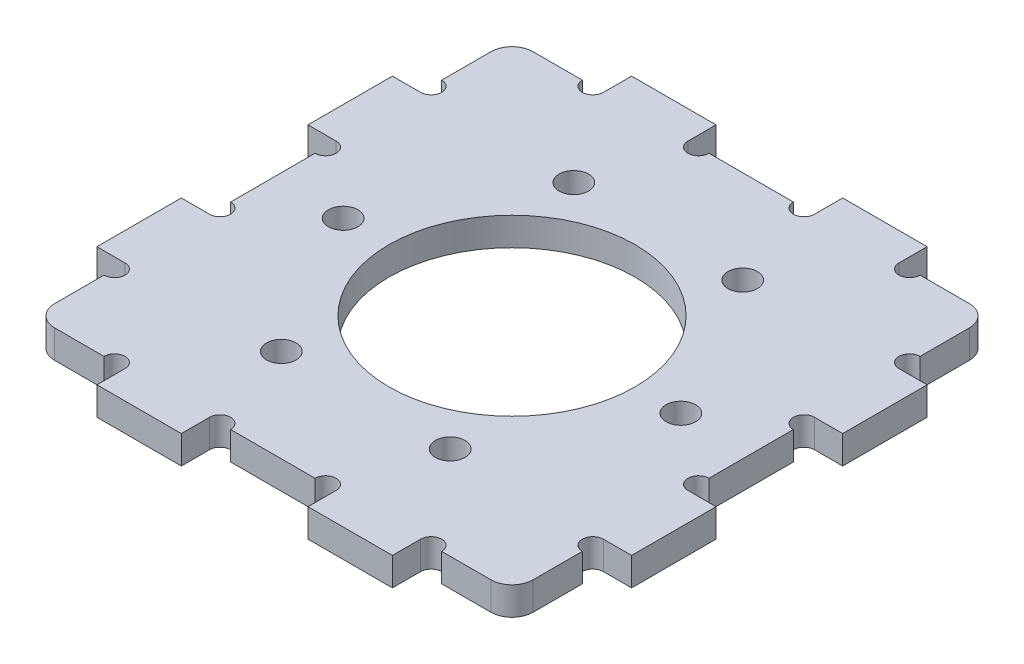
SolidWorks part; units mm, degrees
ref_plane "前视基准面" through (0, 0, 0) normal (0, 0, 1) x (1, 0, 0)
ref_plane "上视基准面" through (0, 0, 0) normal (0, 1, 0) x (1, 0, 0)
ref_plane "右视基准面" through (0, 0, 0) normal (1, 0, 0) x (0, 0, -1)
other "Configuration Table"
sketch "草图1" plane through (0, 0, 0) normal (0, 1, 0) x (1, 0, 0)
  line L1 (-34, -34) -> (34, -34)
  line L2 (-34, -34) -> (-34, 34)
  line L3 (-34, 34) -> (34, 34)
  line L4 (34, -34) -> (34, 34)
  line L5 (-34, -34) -> (34, 34) construction
  line L6 (-34, 34) -> (34, -34) construction
  circle A1 centre (0, 0) radius 17.5
  dimension "D1" = 68
  dimension "D2" = 35
  dimension "D3" = 68
extrude "凸台-拉伸1" add sketch "草图1" along normal blind 4
sketch "草图2" plane through (0, 4, 0) normal (0, 1, 0) x (1, 0, 0)
  line L0 (34, 34) -> (-34, 34) construction
  line L1 (-21, 34) -> (-9, 34)
  line L2 (-21, 34) -> (-21, 38)
  line L3 (-21, 38) -> (-9, 38)
  line L4 (-9, 34) -> (-9, 38)
  line L5 (0, 0) -> (0, 52.3077) construction
  line L6 (21, 34) -> (9, 34)
  line L7 (9, 34) -> (9, 38)
  line L8 (21, 38) -> (9, 38)
  line L9 (21, 34) -> (21, 38)
  line L10 (34, 21) -> (38, 21)
  line L11 (38, 21) -> (38, 9)
  line L12 (34, 21) -> (34, 9)
  line L13 (34, 9) -> (38, 9)
  line L14 (34, -9) -> (38, -9)
  line L15 (38, -21) -> (38, -9)
  line L16 (34, -21) -> (34, -9)
  line L17 (34, -21) -> (38, -21)
  line L18 (21, -34) -> (21, -38)
  line L19 (21, -38) -> (9, -38)
  line L20 (21, -34) -> (9, -34)
  line L21 (9, -34) -> (9, -38)
  line L22 (-9, -34) -> (-9, -38)
  line L23 (-21, -38) -> (-9, -38)
  line L24 (-21, -34) -> (-9, -34)
  line L25 (-21, -34) -> (-21, -38)
  line L26 (-34, -21) -> (-38, -21)
  line L27 (-38, -21) -> (-38, -9)
  line L28 (-34, -21) -> (-34, -9)
  line L29 (-34, -9) -> (-38, -9)
  line L30 (-34, 9) -> (-38, 9)
  line L31 (-38, 21) -> (-38, 9)
  line L32 (-34, 21) -> (-34, 9)
  line L33 (-34, 21) -> (-38, 21)
  dimension "D1" = 4
  dimension "D2" = 12
  dimension "D3" = 18
  dimension "D4" = 4
extrude "凸台-拉伸2" add sketch "草图2" against normal blind 4
sketch "草图3" plane through (0, 4, 0) normal (0, 1, 0) x (1, 0, 0)
  line L0 (-21, 34) -> (-34, 34) construction
  line L1 (9, 34) -> (-9, 34) construction
  line L2 (34, 21) -> (34, 34) construction
  line L3 (34, 34) -> (21, 34) construction
  line L4 (34, -9) -> (34, 9) construction
  line L5 (34, -34) -> (34, -21) construction
  line L6 (21, -34) -> (34, -34) construction
  line L7 (-9, -34) -> (9, -34) construction
  line L8 (-34, -34) -> (-21, -34) construction
  line L9 (-34, -21) -> (-34, -34) construction
  line L10 (-34, 9) -> (-34, -9) construction
  line L11 (-34, 34) -> (-34, 21) construction
  circle A0 centre (-22.5, 34) radius 1.5
  circle A1 centre (-7.5, 34) radius 1.5
  circle A2 centre (7.5, 34) radius 1.5
  circle A4 centre (22.5, 34) radius 1.5
  circle A5 centre (34, 22.5) radius 1.5
  circle A6 centre (34, 7.5) radius 1.5
  circle A7 centre (34, -7.5) radius 1.5
  circle A8 centre (34, -22.5) radius 1.5
  circle A9 centre (22.5, -34) radius 1.5
  circle A10 centre (7.5, -34) radius 1.5
  circle A11 centre (-7.5, -34) radius 1.5
  circle A12 centre (-22.5, -34) radius 1.5
  circle A13 centre (-34, -22.5) radius 1.5
  circle A14 centre (-34, -7.5) radius 1.5
  circle A15 centre (-34, 7.5) radius 1.5
  circle A16 centre (-34, 22.5) radius 1.5
  dimension "D1" = 3
extrude "切除-拉伸1" cut sketch "草图3" against normal blind 4
fillet "圆角1" radius 3 4 edges at (34, 2, 34) (-34, 2, 34) (-34, 2, -34) (34, 2, -34)
sketch "草图4" plane through (0, 4, 0) normal (0, 1, 0) x (1, 0, 0)
  circle A0 centre (0, 0) radius 24 construction
  circle A1 centre (24, 0) radius 2.1
  circle A2 centre (12, -20.7846) radius 2.1
  circle A3 centre (-12, -20.7846) radius 2.1
  circle A4 centre (-24, 0) radius 2.1
  circle A5 centre (-12, 20.7846) radius 2.1
  circle A6 centre (12, 20.7846) radius 2.1
  dimension "D1" = 48
  dimension "D2" = 4.2
  dimension "D3" = 6
extrude "切除-拉伸2" cut sketch "草图4" against normal blind 10
